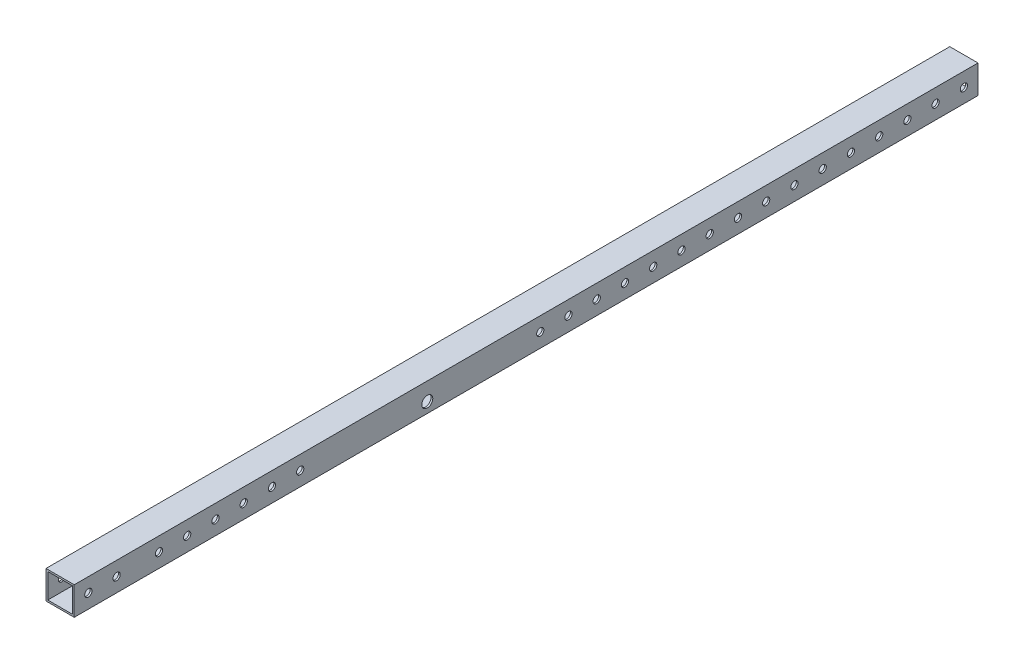
SolidWorks part; units mm, degrees
material "6061 Alloy"
ref_plane "Front Plane" through (0, 0, 0) normal (0, 0, 1) x (1, 0, 0)
ref_plane "Top Plane" through (0, 0, 0) normal (0, 1, 0) x (1, 0, 0)
ref_plane "Right Plane" through (0, 0, 0) normal (1, 0, 0) x (0, 0, -1)
sketch "Sketch1" plane through (0, 0, 0) normal (0, 0, 1) x (1, 0, 0)
  line L1 (0, 0) -> (25.4, 0)
  line L2 (0, 0) -> (0, 25.4)
  line L3 (0, 25.4) -> (25.4, 25.4)
  line L4 (25.4, 0) -> (25.4, 25.4)
  line L5 (1.5875, 23.8125) -> (23.8125, 23.8125)
  line L6 (1.5875, 23.8125) -> (1.5875, 1.5875)
  line L7 (1.5875, 1.5875) -> (23.8125, 1.5875)
  line L8 (23.8125, 23.8125) -> (23.8125, 1.5875)
  dimension "D1" = 25.4
  dimension "D2" = 25.4
  dimension "D3" = 1.5875
  dimension "D4" = 1.5875
  dimension "D5" = 1.5875
  dimension "D6" = 1.5875
extrude "Boss-Extrude1" add sketch "Sketch1" along normal blind 812.8
sketch "Sketch2" plane through (25.4, 0, 0) normal (1, 0, 0) x (0, 0, -1)
  line L0 (0, 0) -> (0, 25.4) construction
  line L1 (-12.7, 12.7) -> (-38.1, 12.7) construction
  line L2 (-406.4, 0) -> (-406.4, 25.4) construction
  line L3 (-812.8, 0) -> (0, 0) construction
  line L4 (-812.8, 25.4) -> (0, 25.4) construction
  circle A0 centre (-12.7, 12.7) radius 3.2639
  circle A1 centre (-38.1, 12.7) radius 3.2639
  circle A2 centre (-774.7, 12.7) radius 3.2639
  circle A3 centre (-800.1, 12.7) radius 3.2639
  point P4 (0, 12.7)
  dimension "D2" = 6.5278
  dimension "D1" = 12.7
  dimension "D4" = 25.4
  dimension "D3" = 2
extrude "Cut-Extrude1" cut sketch "Sketch2" against normal through all
sketch "Sketch3" plane through (25.4, 0, 0) normal (1, 0, 0) x (0, 0, -1)
  line L0 (0, 0) -> (0, 25.4) construction
  line L1 (-812.8, 25.4) -> (0, 25.4) construction
  line L2 (-812.8, 0) -> (-812.8, 25.4) construction
  line L3 (-812.8, 0) -> (0, 0) construction
  line L4 (-736.6, 12.7) -> (-711.2, 12.7) construction
  line L5 (-63.5, 12.7) -> (-88.9, 12.7) construction
  circle A0 centre (-63.5, 12.7) radius 3.2639
  circle A1 centre (-38.1, 12.7) radius 3.2639 construction
  circle A2 centre (-736.6, 12.7) radius 3.2639
  circle A3 centre (-711.2, 12.7) radius 3.2639
  circle A4 centre (-685.8, 12.7) radius 3.2639
  circle A5 centre (-660.4, 12.7) radius 3.2639
  circle A6 centre (-635, 12.7) radius 3.2639
  circle A7 centre (-609.6, 12.7) radius 3.2639
  circle A8 centre (-495.3, 9.271) radius 4.953
  circle A9 centre (-88.9, 12.7) radius 3.2639
  circle A10 centre (-114.3, 12.7) radius 3.2639
  circle A29 centre (-139.7, 12.7) radius 3.2639
  circle A30 centre (-165.1, 12.7) radius 3.2639
  circle A31 centre (-190.5, 12.7) radius 3.2639
  circle A32 centre (-215.9, 12.7) radius 3.2639
  circle A33 centre (-241.3, 12.7) radius 3.2639
  circle A34 centre (-266.7, 12.7) radius 3.2639
  circle A35 centre (-292.1, 12.7) radius 3.2639
  circle A36 centre (-317.5, 12.7) radius 3.2639
  circle A37 centre (-342.9, 12.7) radius 3.2639
  circle A38 centre (-368.3, 12.7) radius 3.2639
  circle A39 centre (-393.7, 12.7) radius 3.2639
  point P29 (0, 0)
  point P35 (0, 0)
  point P37 (0, 0)
  point P43 (0, 0)
  dimension "D3" = 6.5278
  dimension "D8" = 9.906
  dimension "D1" = 63.5
  dimension "D2" = 12.7
  dimension "D4" = 76.2
  dimension "D5" = 12.7
  dimension "D7" = 25.4
  dimension "D9" = 317.5
  dimension "D11" = 25.4
  dimension "D15" = 16.129
  dimension "D6" = 6
  dimension "D10" = 14
extrude "Cut-Extrude2" cut sketch "Sketch3" against normal through all
